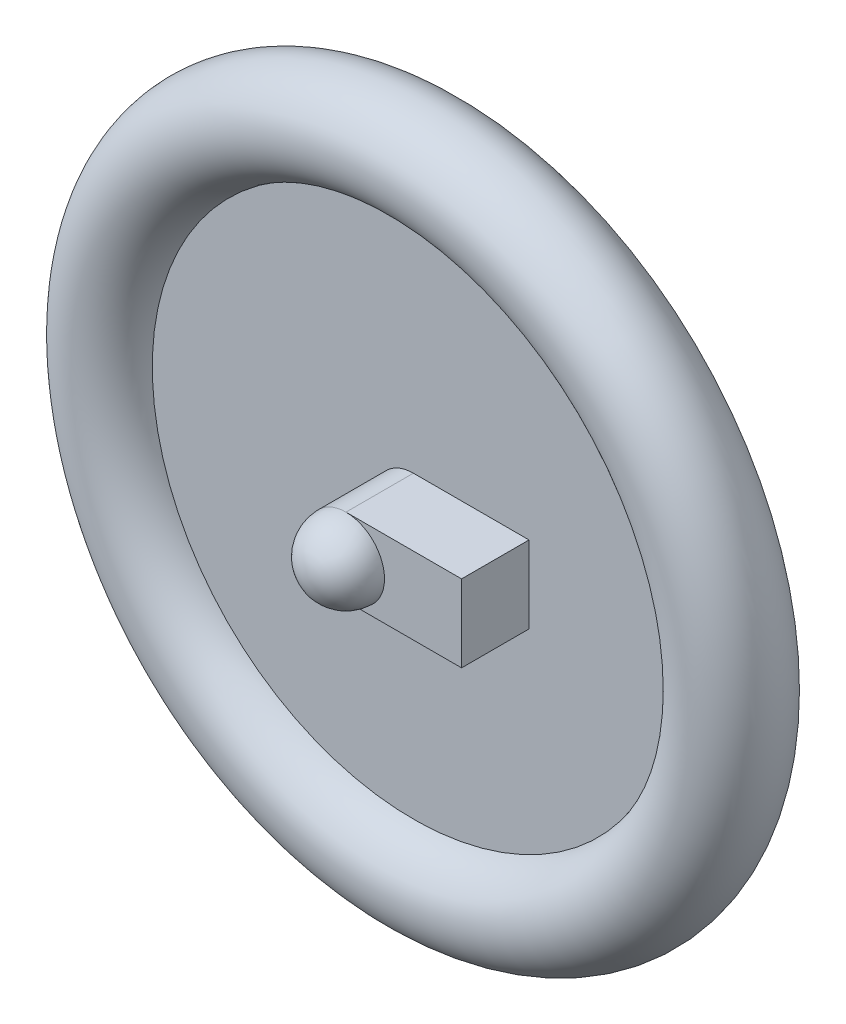
SolidWorks part; units mm, degrees
ref_plane "Front Plane" through (0, 0, 0) normal (0, 0, 1) x (1, 0, 0)
ref_plane "Top Plane" through (0, 0, 0) normal (0, 1, 0) x (1, 0, 0)
ref_plane "Right Plane" through (0, 0, 0) normal (1, 0, 0) x (0, 0, -1)
sketch "Sketch1" plane through (0, 0, 0) normal (0, 1, 0) x (1, 0, 0)
  line L0 (0, 0) -> (0, 37.2507) construction
  circle A0 centre (80, 0) radius 12.5
  dimension "D2" = 25
  dimension "D1" = 80
revolve "Revolve1" add sketch "Sketch1" angle 360 about L0
sketch "Sketch2" plane through (0, 0, 0) normal (0, 1, 0) x (1, 0, 0)
  line L1 (-80, -2.5) -> (80, -2.5)
  line L2 (-80, -2.5) -> (-80, 2.5)
  line L3 (-80, 2.5) -> (80, 2.5)
  line L4 (80, -2.5) -> (80, 2.5)
  point P4 (0, -2.5)
  point P6 (80, 0)
  dimension "D1" = 160
  dimension "D2" = 5
extrude "Boss-Extrude1" add sketch "Sketch2" along normal up to surface and the other way up to surface
sketch "Sketch4" plane through (0, 0, 0) normal (0, 1, 0) x (1, 0, 0)
  line L0 (0, -30) -> (0, 0)
  line L2 (0, 0) -> (10, 0)
  line L3 (10, 0) -> (10, -20)
  arc A0 (0, -30) -> (10, -20) centre (0, -20) ccw
  dimension "D1" = 10
  dimension "D2" = 20
revolve "Revolve2" add sketch "Sketch4" angle 360 about L0
sketch "Sketch6" plane through (0, 0, 0) normal (1, 0, 0) x (0, 0, -1)
  line L1 (-20, -10) -> (-2.5, -10)
  line L2 (-20, -10) -> (-20, 10)
  line L3 (-20, 10) -> (-2.5, 10)
  line L4 (-2.5, -10) -> (-2.5, 10)
extrude "Boss-Extrude2" add sketch "Sketch6" along normal blind 30
